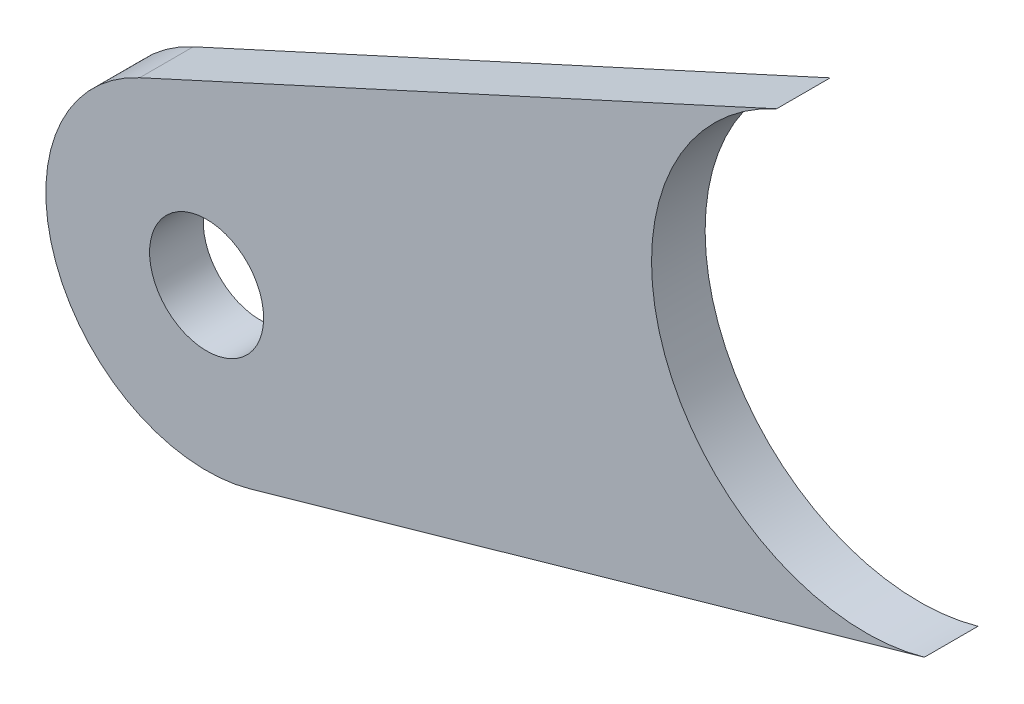
SolidWorks part; units mm, degrees
ref_plane "Front Plane" through (0, 0, 0) normal (0, 0, 1) x (1, 0, 0)
ref_plane "Top Plane" through (0, 0, 0) normal (0, 1, 0) x (1, 0, 0)
ref_plane "Right Plane" through (0, 0, 0) normal (1, 0, 0) x (0, 0, -1)
sketch "Sketch2" plane through (0, 0, 0) normal (0, 0, 1) x (1, 0, 0)
  line L0 (101.5644, 0) -> (140.6269, 14.3894) construction
  line L1 (101.5644, 0) -> (140.6269, 14.3894)
  line L2 (97.5999, 8.6607) -> (135.3409, 25.9371)
  line L3 (104.1656, -9.1629) -> (144.0952, 2.1722)
  circle A0 centre (101.5644, 0) radius 3.3782 construction
  circle A1 centre (101.5644, 0) radius 3.3782
  circle A2 centre (140.6269, 14.3894) radius 12.7
  circle A4 centre (101.5644, 0) radius 9.525
  arc A5 (101.5644, -9.525) -> (103.8502, 9.2467) centre (101.5644, 0) ccw construction
  dimension "D1" = 25.4
  dimension "D2" = 19.05
extrude "Boss-Extrude1" add sketch "Sketch2" along normal blind 3.175
